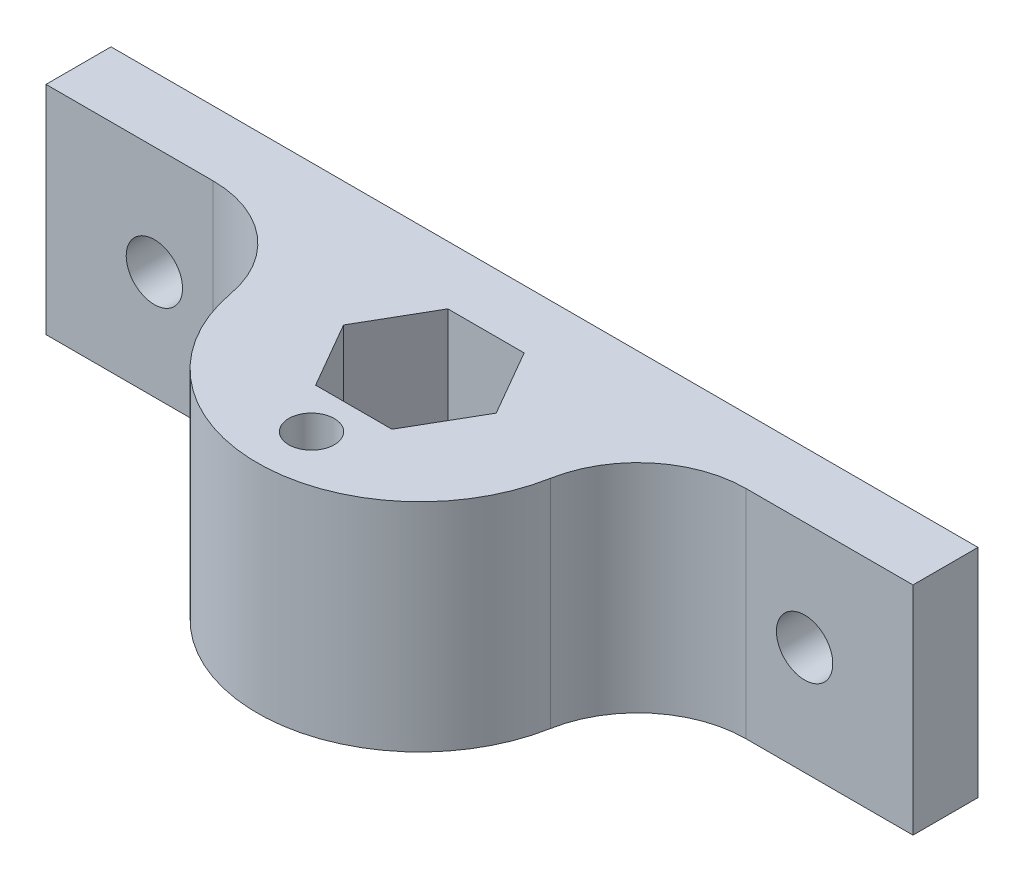
SolidWorks part; units mm, degrees
material "ABS"
ref_plane "Front Plane" through (0, 0, 0) normal (0, 0, 1) x (1, 0, 0)
ref_plane "Top Plane" through (0, 0, 0) normal (0, 1, 0) x (1, 0, 0)
ref_plane "Right Plane" through (0, 0, 0) normal (1, 0, 0) x (0, 0, -1)
sketch "Sketch1" plane through (0, 0, 0) normal (0, 1, 0) x (1, 0, 0)
  line L0 (0, 0) -> (40, 0)
  line L1 (40, 0) -> (40, -6)
  line L2 (40, -6) -> (13.9553, -6)
  line L3 (0, 0) -> (-40, 0)
  line L4 (-40, 0) -> (-40, -6)
  line L5 (-40, -6) -> (-13.9553, -6)
  line L6 (0, 0) -> (0, -11.5) construction
  arc A0 (-13.9553, -6) -> (13.9553, -6) centre (0, -11.5) ccw
  dimension "D4" = 15
  dimension "D1" = 11.5
  dimension "D2" = 80
  dimension "D3" = 6
extrude "Boss-Extrude1" add sketch "Sketch1" along normal blind 20
fillet "Fillet1" radius 10 2 edges at (-13.9553, 10, 6) (13.9553, 10, 6)
sketch "Sketch2" plane through (0, 20, 0) normal (0, 1, 0) x (1, 0, 0)
  line L1 (-7.0437, -11.5) -> (-3.5218, -17.6)
  line L2 (-3.5218, -17.6) -> (3.5218, -17.6)
  line L3 (3.5218, -17.6) -> (7.0437, -11.5)
  line L4 (7.0437, -11.5) -> (3.5218, -5.4)
  line L5 (3.5218, -5.4) -> (-3.5218, -5.4)
  line L6 (-3.5218, -5.4) -> (-7.0437, -11.5)
  circle A0 centre (0, -11.5) radius 6.1 construction
  dimension "D1" = 12.2
extrude "Cut-Extrude1" cut sketch "Sketch2" against normal through all
sketch "Sketch3" plane through (0, 20, 0) normal (0, 1, 0) x (1, 0, 0)
  line L0 (0, 0) -> (0, -21.5) construction
  line L1 (40, 0) -> (-40, 0) construction
  circle A0 centre (0, -21.5) radius 2.1
  dimension "D1" = 4.2
  dimension "D2" = 21.5
extrude "Cut-Extrude2" cut sketch "Sketch3" against normal through all
sketch "Sketch4" plane through (0, 0, 0) normal (0, 0, -1) x (-1, 0, 0)
  line L0 (-40, 10) -> (-30, 10) construction
  line L1 (-40, 20) -> (-40, 0) construction
  line L2 (-30, 10) -> (30, 10) construction
  line L3 (30, 10) -> (40, 10) construction
  line L4 (40, 20) -> (40, 0) construction
  circle A0 centre (-30, 10) radius 2.6
  circle A1 centre (30, 10) radius 2.6
  dimension "D1" = 5.2
  dimension "D2" = 10
extrude "Cut-Extrude3" cut sketch "Sketch4" against normal through all
